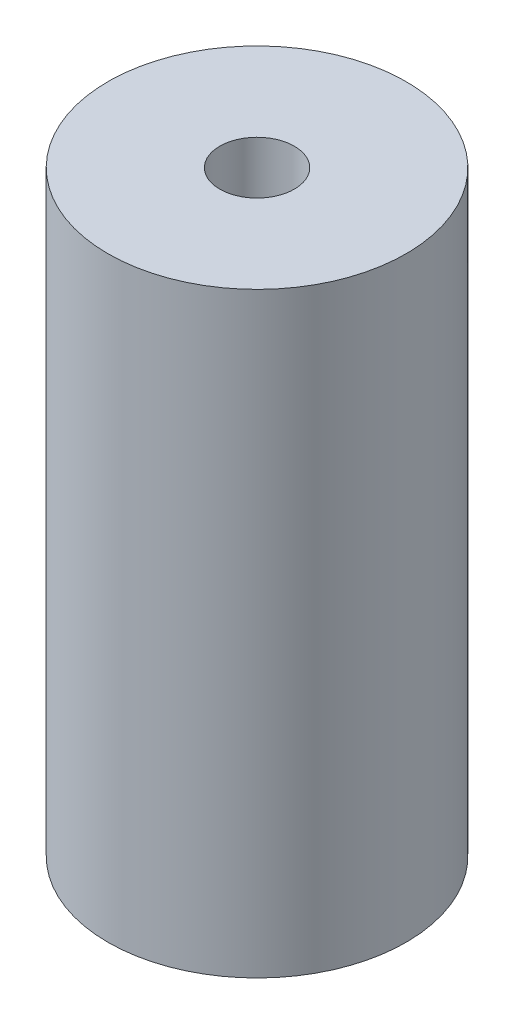
SolidWorks part; units mm, degrees
ref_plane "前视基准面" through (0, 0, 0) normal (0, 0, 1) x (1, 0, 0)
ref_plane "上视基准面" through (0, 0, 0) normal (0, 1, 0) x (1, 0, 0)
ref_plane "右视基准面" through (0, 0, 0) normal (1, 0, 0) x (0, 0, -1)
other "Configuration Table"
sketch "草图1" plane through (0, 0, 0) normal (0, 1, 0) x (1, 0, 0)
  circle A0 centre (0, 0) radius 10
  dimension "D1" = 20
extrude "凸台-拉伸1" add sketch "草图1" along normal blind 40
sketch "草图3" plane through (0, 40, 0) normal (0, 1, 0) x (1, 0, 0)
  circle A0 centre (0, 0) radius 2.5
extrude "切除-拉伸8" cut sketch "草图3" against normal blind 20
sketch "草图4" plane through (0, 0, 0) normal (0, 0, 1) x (1, 0, 0)
  line L0 (-10, 40) -> (-10, 0) construction
  line L2 (2.5, 40) -> (-2.5, 40) construction
  circle A0 centre (0, 20) radius 2.5
  point P6 (1.2482, 0)
  point P7 (0.9911, 18.4128)
  dimension "D1" = 10
  dimension "D2" = 20
extrude "切除-拉伸9" cut sketch "草图4" against normal blind 20
